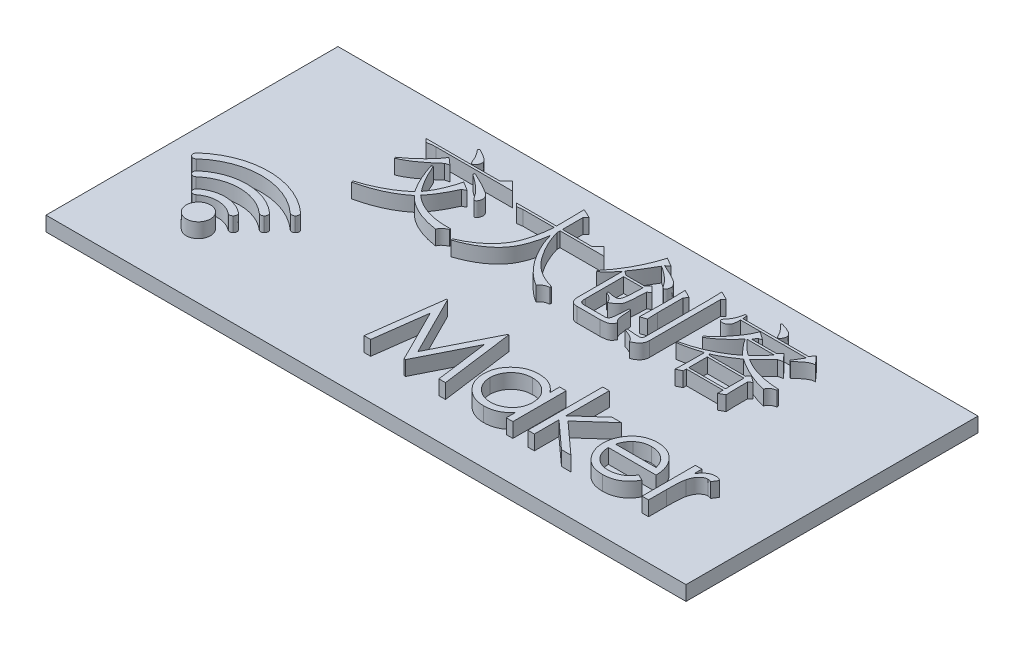
SolidWorks part; units mm, degrees
ref_plane "前视" through (0, 0, 0) normal (0, 0, 1) x (1, 0, 0)
ref_plane "上视" through (0, 0, 0) normal (0, 1, 0) x (1, 0, 0)
ref_plane "右视" through (0, 0, 0) normal (1, 0, 0) x (0, 0, -1)
sketch "草图1" plane through (0, 0, 0) normal (0, 1, 0) x (1, 0, 0)
  line L1 (-65.5265, 11.4668) -> (-15.5265, 11.4668)
  line L2 (-65.5265, 11.4668) -> (-65.5265, 31.4668)
  line L3 (-65.5265, 31.4668) -> (-15.5265, 31.4668)
  line L4 (-15.5265, 11.4668) -> (-15.5265, 31.4668)
  dimension "D1" = 50
  dimension "D2" = 20
extrude "凸台-拉伸1" add sketch "草图1" along normal blind 1
sketch "草图2" plane through (0, 1, 0) normal (0, 1, 0) x (1, 0, 0)
  line L2 (-58.0758, 16.832) -> (-58.0615, 16.8463)
  line L3 (-63.0448, 18.9594) -> (-63.059, 18.9736)
  line L4 (-61.9825, 17.897) -> (-61.9966, 17.9112)
  line L5 (-60.9175, 16.832) -> (-60.9317, 16.8463)
  line L6 (-57.0108, 17.897) -> (-56.9966, 17.9112)
  line L7 (-55.9484, 18.9594) -> (-55.9342, 18.9736)
  arc A0 (-55.9425, 19.3209) -> (-55.9342, 18.9736) centre (-56.1039, 19.1433) cw
  arc A1 (-58.3938, 16.8131) -> (-60.5994, 16.8131) centre (-59.4966, 15.4112) ccw
  arc A2 (-58.0826, 17.2045) -> (-60.9106, 17.2045) centre (-59.4966, 15.4112) ccw
  arc A3 (-57.3382, 17.8859) -> (-61.655, 17.8859) centre (-59.4966, 15.4112) ccw
  arc A4 (-57.0085, 18.2617) -> (-61.9847, 18.2617) centre (-59.4966, 15.4112) ccw
  arc A5 (-56.2795, 18.9515) -> (-62.7137, 18.9515) centre (-59.4966, 15.4112) ccw
  arc A6 (-55.9425, 19.3209) -> (-63.0507, 19.3209) centre (-59.4966, 15.4112) ccw
  circle A7 centre (-59.4966, 15.8747) radius 0.8309
  circle A8 centre (-59.4966, 15.4112) radius 1.7837 construction
  circle A9 centre (-59.4966, 15.4112) radius 2.2837 construction
  circle A10 centre (-59.4966, 15.4112) radius 3.2837 construction
  circle A11 centre (-59.4966, 15.4112) radius 3.7837 construction
  circle A12 centre (-59.4966, 15.4112) radius 4.7837 construction
  circle A13 centre (-59.4966, 15.4112) radius 5.2837 construction
  arc A14 (-56.2795, 18.9515) -> (-55.9484, 18.9594) centre (-56.1181, 19.1291) ccw
  arc A15 (-57.0085, 18.2617) -> (-56.9966, 17.9112) centre (-57.1663, 18.0809) cw
  arc A16 (-57.3382, 17.8859) -> (-57.0108, 17.897) centre (-57.1805, 18.0667) ccw
  arc A17 (-58.0826, 17.2045) -> (-58.0615, 16.8463) centre (-58.2312, 17.016) cw
  arc A18 (-58.3938, 16.8131) -> (-58.0758, 16.832) centre (-58.2455, 17.0017) ccw
  arc A19 (-63.0507, 19.3209) -> (-63.059, 18.9736) centre (-62.8893, 19.1433) ccw
  arc A20 (-62.7137, 18.9515) -> (-63.0448, 18.9594) centre (-62.8751, 19.1291) cw
  arc A21 (-61.9847, 18.2617) -> (-61.9966, 17.9112) centre (-61.8269, 18.0809) ccw
  arc A22 (-61.655, 17.8859) -> (-61.9825, 17.897) centre (-61.8127, 18.0667) cw
  arc A23 (-60.9106, 17.2045) -> (-60.9317, 16.8463) centre (-60.762, 17.016) ccw
  arc A24 (-60.5994, 16.8131) -> (-60.9175, 16.832) centre (-60.7478, 17.0017) cw
  text T0 "交大创客\r\n     Maker" font "Century Gothic" height 5
  point P3 (-57.2129, 15.4112)
  point P5 (-56.2129, 15.4112)
  point P7 (-55.7129, 15.4112)
  point P9 (-54.7129, 15.4112)
  point P14 (-54.2129, 15.4112)
  point P17 (-57.7909, 15.9327)
  point P36 (-55.7605, 19.1473)
  point P39 (-56.114, 18.7938)
  point P42 (-56.8212, 18.0866)
  point P45 (-57.1747, 17.7331)
  dimension "D4" = 0.24
  dimension "D1" = 0.5
  dimension "D2" = 1
  dimension "D3" = 0.5
  dimension "D6" = 1
  dimension "D7" = 0.5
extrude "凸台-拉伸2" add sketch "草图2" along normal blind 1
sketch "草图3" plane through (0, 1, 0) normal (0, 1, 0) x (1, 0, 0)
  line L0 (-15.5265, 31.4668) -> (-65.5265, 31.4668) construction
  line L1 (-21.6895, 31.4668) -> (-15.5265, 31.4668)
  line L2 (-21.6895, 31.4668) -> (-21.6895, 11.4668)
  line L3 (-21.6895, 11.4668) -> (-15.5265, 11.4668)
  line L4 (-15.5265, 31.4668) -> (-15.5265, 11.4668)
extrude "切除-拉伸1" cut sketch "草图3" against normal blind 1
